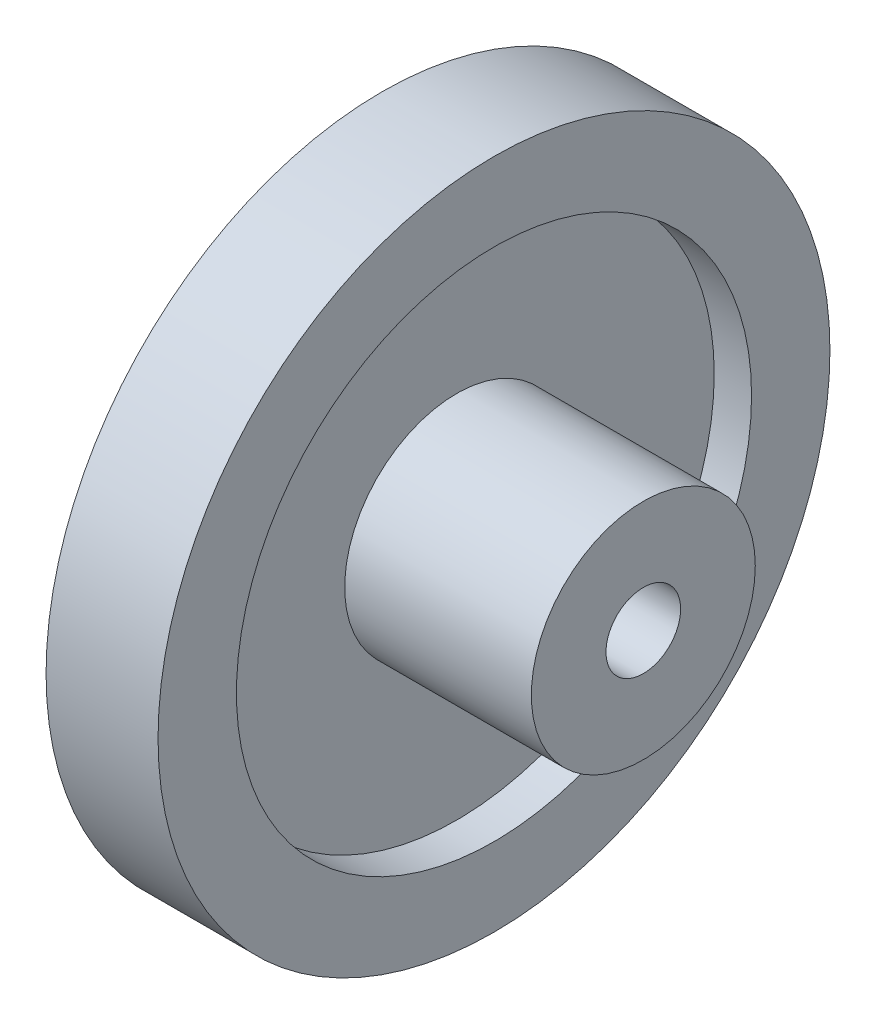
SolidWorks part; units mm, degrees
ref_plane "Plan de face" through (0, 0, 0) normal (0, 0, 1) x (1, 0, 0)
ref_plane "Plan de dessus" through (0, 0, 0) normal (0, 1, 0) x (1, 0, 0)
ref_plane "Plan de droite" through (0, 0, 0) normal (1, 0, 0) x (0, 0, -1)
sketch "Esquisse2" plane through (0, 0, 0) normal (1, 0, 0) x (0, 0, -1)
  arc A0 (8.9927, 0.363) -> (8.9699, 0.736) centre (0, 0) ccw
  arc A1 (8.7729, 2.0092) -> (8.6819, 2.3717) centre (0, 0) ccw
  arc A2 (8.2543, 3.587) -> (8.0983, 3.9266) centre (0, 0) ccw
  arc A3 (7.4547, 5.0426) -> (7.2389, 5.3478) centre (0, 0) ccw
  arc A4 (6.4012, 6.3266) -> (6.133, 6.5869) centre (0, 0) ccw
  arc A5 (5.1297, 7.395) -> (4.8182, 7.6016) centre (0, 0) ccw
  arc A6 (3.6835, 8.2117) -> (3.3394, 8.3575) centre (0, 0) ccw
  arc A7 (2.1119, 8.7487) -> (1.7468, 8.8289) centre (0, 0) ccw
  arc A8 (0.4683, 8.9878) -> (0.0948, 8.9995) centre (0, 0) ccw
  arc A9 (-1.1911, 8.9208) -> (-1.5605, 8.8637) centre (0, 0) ccw
  arc A10 (-2.8101, 8.5501) -> (-3.1626, 8.426) centre (0, 0) ccw
  arc A11 (-4.3333, 7.8881) -> (-4.657, 7.7014) centre (0, 0) ccw
  arc A12 (-5.7089, 6.9576) -> (-5.9929, 6.7146) centre (0, 0) ccw
  arc A13 (-6.8902, 5.7901) -> (-7.1246, 5.499) centre (0, 0) ccw
  arc A14 (-7.8368, 4.4254) -> (-8.0138, 4.0963) centre (0, 0) ccw
  arc A15 (-8.5165, 2.9101) -> (-8.63, 2.554) centre (0, 0) ccw
  arc A16 (-8.9063, 1.2956) -> (-8.9524, 0.9247) centre (0, 0) ccw
  arc A17 (-8.9927, -0.363) -> (-8.9699, -0.736) centre (0, 0) ccw
  arc A18 (-8.7729, -2.0092) -> (-8.6819, -2.3717) centre (0, 0) ccw
  arc A19 (-8.2543, -3.587) -> (-8.0983, -3.9266) centre (0, 0) ccw
  arc A20 (-7.4547, -5.0426) -> (-7.2389, -5.3478) centre (0, 0) ccw
  arc A21 (-6.4012, -6.3266) -> (-6.133, -6.5869) centre (0, 0) ccw
  arc A22 (-5.1297, -7.395) -> (-4.8182, -7.6016) centre (0, 0) ccw
  arc A23 (-3.6835, -8.2117) -> (-3.3394, -8.3575) centre (0, 0) ccw
  arc A24 (-2.1119, -8.7487) -> (-1.7468, -8.8289) centre (0, 0) ccw
  arc A25 (-0.4683, -8.9878) -> (-0.0948, -8.9995) centre (0, 0) ccw
  arc A26 (1.1911, -8.9208) -> (1.5605, -8.8637) centre (0, 0) ccw
  arc A27 (2.8101, -8.5501) -> (3.1626, -8.426) centre (0, 0) ccw
  arc A28 (4.3333, -7.8881) -> (4.657, -7.7014) centre (0, 0) ccw
  arc A29 (5.7089, -6.9576) -> (5.9929, -6.7146) centre (0, 0) ccw
  arc A30 (6.8902, -5.7901) -> (7.1246, -5.499) centre (0, 0) ccw
  arc A31 (7.8368, -4.4254) -> (8.0138, -4.0963) centre (0, 0) ccw
  arc A32 (8.5165, -2.9101) -> (8.63, -2.554) centre (0, 0) ccw
  arc A33 (8.9063, -1.2956) -> (8.9524, -0.9247) centre (0, 0) ccw
  arc A34 (7.987, 0) -> (7.8742, -0.1109) centre (7.9867, -0.1125) ccw
  arc A35 (7.8657, -0.3818) -> (7.9719, -0.4996) centre (7.9781, -0.3873) ccw
  arc A36 (7.8657, -0.3818) -> (7.8742, -0.1109) centre (0, 0) ccw
  arc A37 (7.851, 1.4676) -> (7.7605, 1.3379) centre (7.8714, 1.357) ccw
  arc A38 (7.802, 1.07) -> (7.928, 0.9737) centre (7.9134, 1.0853) ccw
  arc A39 (7.802, 1.07) -> (7.7605, 1.3379) centre (0, 0) ccw
  arc A40 (7.4477, 2.8852) -> (7.3826, 2.7411) centre (7.488, 2.7802) ccw
  arc A41 (7.4725, 2.4854) -> (7.6141, 2.4139) centre (7.5793, 2.5209) ccw
  arc A42 (7.4725, 2.4854) -> (7.3826, 2.7411) centre (0, 0) ccw
  arc A43 (6.7907, 4.2046) -> (6.7532, 4.0509) centre (6.8497, 4.1088) ccw
  arc A44 (6.8886, 3.8161) -> (7.0409, 3.7719) centre (6.987, 3.8706) ccw
  arc A45 (6.8886, 3.8161) -> (6.7532, 4.0509) centre (0, 0) ccw
  arc A46 (5.9025, 5.3808) -> (5.8938, 5.2229) centre (5.978, 5.2975) ccw
  arc A47 (6.0701, 5.0169) -> (6.2279, 5.0014) centre (6.1568, 5.0886) ccw
  arc A48 (6.0701, 5.0169) -> (5.8938, 5.2229) centre (0, 0) ccw
  arc A49 (4.8132, 6.3738) -> (4.8338, 6.2169) centre (4.9028, 6.3057) ccw
  arc A50 (5.0449, 6.0469) -> (5.2029, 6.0607) centre (5.117, 6.1333) ccw
  arc A51 (5.0449, 6.0469) -> (4.8338, 6.2169) centre (0, 0) ccw
  arc A52 (3.5601, 7.1497) -> (3.6091, 6.9993) centre (3.6607, 7.0993) ccw
  arc A53 (3.8479, 6.8709) -> (4.0007, 6.9135) centre (3.9028, 6.9691) ccw
  arc A54 (3.8479, 6.8709) -> (3.6091, 6.9993) centre (0, 0) ccw
  arc A55 (2.1857, 7.6821) -> (2.2616, 7.5433) centre (2.2939, 7.651) ccw
  arc A56 (2.5198, 7.461) -> (2.6622, 7.5309) centre (2.5558, 7.5676) ccw
  arc A57 (2.5198, 7.461) -> (2.2616, 7.5433) centre (0, 0) ccw
  arc A58 (0.7369, 7.9529) -> (0.837, 7.8304) centre (0.8489, 7.9423) ccw
  arc A59 (1.106, 7.797) -> (1.2331, 7.8918) centre (1.1218, 7.9083) ccw
  arc A60 (1.106, 7.797) -> (0.837, 7.8304) centre (0, 0) ccw
  arc A61 (-0.7369, 7.9529) -> (-0.6161, 7.8509) centre (-0.6249, 7.963) ccw
  arc A62 (-0.3455, 7.8674) -> (-0.2381, 7.984) centre (-0.3505, 7.9798) ccw
  arc A63 (-0.3455, 7.8674) -> (-0.6161, 7.8509) centre (0, 0) ccw
  arc A64 (-2.1857, 7.6821) -> (-2.0482, 7.604) centre (-2.0775, 7.7126) ccw
  arc A65 (-1.7853, 7.67) -> (-1.7011, 7.8044) centre (-1.8108, 7.7795) ccw
  arc A66 (-1.7853, 7.67) -> (-2.0482, 7.604) centre (0, 0) ccw
  arc A67 (-3.5601, 7.1497) -> (-3.4106, 7.0981) centre (-3.4593, 7.1996) ccw
  arc A68 (-3.1642, 7.2113) -> (-3.1062, 7.3589) centre (-3.2095, 7.3143) ccw
  arc A69 (-3.1642, 7.2113) -> (-3.4106, 7.0981) centre (0, 0) ccw
  arc A70 (-4.8132, 6.3738) -> (-4.6568, 6.3506) centre (-4.7233, 6.4413) ccw
  arc A71 (-4.4354, 6.5071) -> (-4.4055, 6.6628) centre (-4.4988, 6.6001) ccw
  arc A72 (-4.4354, 6.5071) -> (-4.6568, 6.3506) centre (0, 0) ccw
  arc A73 (-5.9025, 5.3808) -> (-5.7444, 5.3868) centre (-5.8265, 5.4637) ccw
  arc A74 (-5.5556, 5.5813) -> (-5.5547, 5.7399) centre (-5.635, 5.661) ccw
  arc A75 (-5.5556, 5.5813) -> (-5.7444, 5.3868) centre (0, 0) ccw
  arc A76 (-6.7907, 4.2046) -> (-6.6364, 4.2395) centre (-6.7312, 4.3001) ccw
  arc A77 (-6.4866, 4.4654) -> (-6.5149, 4.6215) centre (-6.5792, 4.5292) ccw
  arc A78 (-6.4866, 4.4654) -> (-6.6364, 4.2395) centre (0, 0) ccw
  arc A79 (-7.4477, 2.8852) -> (-7.3024, 2.9479) centre (-7.4067, 2.99) ccw
  arc A80 (-7.1966, 3.1975) -> (-7.2531, 3.3457) centre (-7.2995, 3.2432) ccw
  arc A81 (-7.1966, 3.1975) -> (-7.3024, 2.9479) centre (0, 0) ccw
  arc A82 (-7.851, 1.4676) -> (-7.7198, 1.5559) centre (-7.83, 1.5781) ccw
  arc A83 (-7.6616, 1.8207) -> (-7.7444, 1.956) centre (-7.7711, 1.8467) ccw
  arc A84 (-7.6616, 1.8207) -> (-7.7198, 1.5559) centre (0, 0) ccw
  arc A85 (-7.987, 0) -> (-7.8742, 0.1109) centre (-7.9867, 0.1125) ccw
  arc A86 (-7.8657, 0.3818) -> (-7.9719, 0.4996) centre (-7.9781, 0.3873) ccw
  arc A87 (-7.8657, 0.3818) -> (-7.8742, 0.1109) centre (0, 0) ccw
  arc A88 (-7.851, -1.4676) -> (-7.7605, -1.3379) centre (-7.8714, -1.357) ccw
  arc A89 (-7.802, -1.07) -> (-7.928, -0.9737) centre (-7.9134, -1.0853) ccw
  arc A90 (-7.802, -1.07) -> (-7.7605, -1.3379) centre (0, 0) ccw
  arc A91 (-7.4477, -2.8852) -> (-7.3826, -2.7411) centre (-7.488, -2.7802) ccw
  arc A92 (-7.4725, -2.4854) -> (-7.6141, -2.4139) centre (-7.5793, -2.5209) ccw
  arc A93 (-7.4725, -2.4854) -> (-7.3826, -2.7411) centre (0, 0) ccw
  arc A94 (-6.7907, -4.2046) -> (-6.7532, -4.0509) centre (-6.8497, -4.1088) ccw
  arc A95 (-6.8886, -3.8161) -> (-7.0409, -3.7719) centre (-6.987, -3.8706) ccw
  arc A96 (-6.8886, -3.8161) -> (-6.7532, -4.0509) centre (0, 0) ccw
  arc A97 (-5.9025, -5.3808) -> (-5.8938, -5.2229) centre (-5.978, -5.2975) ccw
  arc A98 (-6.0701, -5.0169) -> (-6.2279, -5.0014) centre (-6.1568, -5.0886) ccw
  arc A99 (-6.0701, -5.0169) -> (-5.8938, -5.2229) centre (0, 0) ccw
  arc A100 (-4.8132, -6.3738) -> (-4.8338, -6.2169) centre (-4.9028, -6.3057) ccw
  arc A101 (-5.0449, -6.0469) -> (-5.2029, -6.0607) centre (-5.117, -6.1333) ccw
  arc A102 (-5.0449, -6.0469) -> (-4.8338, -6.2169) centre (0, 0) ccw
  arc A103 (-3.5601, -7.1497) -> (-3.6091, -6.9993) centre (-3.6607, -7.0993) ccw
  arc A104 (-3.8479, -6.8709) -> (-4.0007, -6.9135) centre (-3.9028, -6.9691) ccw
  arc A105 (-3.8479, -6.8709) -> (-3.6091, -6.9993) centre (0, 0) ccw
  arc A106 (-2.1857, -7.6821) -> (-2.2616, -7.5433) centre (-2.2939, -7.651) ccw
  arc A107 (-2.5198, -7.461) -> (-2.6622, -7.5309) centre (-2.5558, -7.5676) ccw
  arc A108 (-2.5198, -7.461) -> (-2.2616, -7.5433) centre (0, 0) ccw
  arc A109 (-0.7369, -7.9529) -> (-0.837, -7.8304) centre (-0.8489, -7.9423) ccw
  arc A110 (-1.106, -7.797) -> (-1.2331, -7.8918) centre (-1.1218, -7.9083) ccw
  arc A111 (-1.106, -7.797) -> (-0.837, -7.8304) centre (0, 0) ccw
  arc A112 (0.7369, -7.9529) -> (0.6161, -7.8509) centre (0.6249, -7.963) ccw
  arc A113 (0.3455, -7.8674) -> (0.2381, -7.984) centre (0.3505, -7.9798) ccw
  arc A114 (0.3455, -7.8674) -> (0.6161, -7.8509) centre (0, 0) ccw
  arc A115 (2.1857, -7.6821) -> (2.0482, -7.604) centre (2.0775, -7.7126) ccw
  arc A116 (1.7853, -7.67) -> (1.7011, -7.8044) centre (1.8108, -7.7795) ccw
  arc A117 (1.7853, -7.67) -> (2.0482, -7.604) centre (0, 0) ccw
  arc A118 (3.5601, -7.1497) -> (3.4106, -7.0981) centre (3.4593, -7.1996) ccw
  arc A119 (3.1642, -7.2113) -> (3.1062, -7.3589) centre (3.2095, -7.3143) ccw
  arc A120 (3.1642, -7.2113) -> (3.4106, -7.0981) centre (0, 0) ccw
  arc A121 (4.8132, -6.3738) -> (4.6568, -6.3506) centre (4.7233, -6.4413) ccw
  arc A122 (4.4354, -6.5071) -> (4.4055, -6.6628) centre (4.4988, -6.6001) ccw
  arc A123 (4.4354, -6.5071) -> (4.6568, -6.3506) centre (0, 0) ccw
  arc A124 (5.9025, -5.3808) -> (5.7444, -5.3868) centre (5.8265, -5.4637) ccw
  arc A125 (5.5556, -5.5813) -> (5.5547, -5.7399) centre (5.635, -5.661) ccw
  arc A126 (5.5556, -5.5813) -> (5.7444, -5.3868) centre (0, 0) ccw
  arc A127 (6.7907, -4.2046) -> (6.6364, -4.2395) centre (6.7312, -4.3001) ccw
  arc A128 (6.4866, -4.4654) -> (6.5149, -4.6215) centre (6.5792, -4.5292) ccw
  arc A129 (6.4866, -4.4654) -> (6.6364, -4.2395) centre (0, 0) ccw
  arc A130 (7.4477, -2.8852) -> (7.3024, -2.9479) centre (7.4067, -2.99) ccw
  arc A131 (7.1966, -3.1975) -> (7.2531, -3.3457) centre (7.2995, -3.2432) ccw
  arc A132 (7.1966, -3.1975) -> (7.3024, -2.9479) centre (0, 0) ccw
  arc A133 (7.851, -1.4676) -> (7.7198, -1.5559) centre (7.83, -1.5781) ccw
  arc A134 (7.6616, -1.8207) -> (7.7444, -1.956) centre (7.7711, -1.8467) ccw
  arc A135 (7.6616, -1.8207) -> (7.7198, -1.5559) centre (0, 0) ccw
  circle A136 centre (0, 0) radius 1
  spline S0 degree 3 poles (7.987, 0) (8.0286, 0) (8.2037, 0.0282) (8.4818, 0.1115) (8.7713, 0.2415) (8.9323, 0.3284) (8.9927, 0.363) knots 0 0 0 0 0.124841 0.528779 0.867842 1.076016 1.076016 1.076016 1.076016
  spline S1 degree 3 poles (7.928, 0.9737) (7.9687, 0.9787) (8.146, 0.9721) (8.4321, 0.9233) (8.7354, 0.8295) (8.9058, 0.7629) (8.9699, 0.736) knots 0 0 0 0 0.124841 0.528779 0.867842 1.076016 1.076016 1.076016 1.076016
  spline S2 degree 3 poles (7.851, 1.4676) (7.8919, 1.4753) (8.0589, 1.5352) (8.3169, 1.6682) (8.5776, 1.8491) (8.7199, 1.9642) (8.7729, 2.0092) knots 0 0 0 0 0.124841 0.528779 0.867842 1.076016 1.076016 1.076016 1.076016
  spline S3 degree 3 poles (7.6141, 2.4139) (7.6532, 2.4263) (7.8287, 2.4523) (8.1189, 2.4569) (8.4342, 2.4205) (8.6139, 2.3863) (8.6819, 2.3717) knots 0 0 0 0 0.124841 0.528779 0.867842 1.076016 1.076016 1.076016 1.076016
  spline S4 degree 3 poles (7.4477, 2.8852) (7.4865, 2.9003) (7.6396, 2.9898) (7.8687, 3.168) (8.0918, 3.3938) (8.2105, 3.533) (8.2543, 3.587) knots 0 0 0 0 0.124841 0.528779 0.867842 1.076016 1.076016 1.076016 1.076016
  spline S5 degree 3 poles (7.0409, 3.7719) (7.0771, 3.7913) (7.2448, 3.8491) (7.5292, 3.9069) (7.8458, 3.9291) (8.0288, 3.9285) (8.0983, 3.9266) knots 0 0 0 0 0.124841 0.528779 0.867842 1.076016 1.076016 1.076016 1.076016
  spline S6 degree 3 poles (6.7907, 4.2046) (6.8261, 4.2265) (6.9601, 4.3427) (7.1526, 4.5599) (7.3304, 4.8229) (7.4215, 4.9815) (7.4547, 5.0426) knots 0 0 0 0 0.124841 0.528779 0.867842 1.076016 1.076016 1.076016 1.076016
  spline S7 degree 3 poles (6.2279, 5.0014) (6.2599, 5.0271) (6.4141, 5.1148) (6.6831, 5.2239) (6.9903, 5.3039) (7.1702, 5.3369) (7.2389, 5.3478) knots 0 0 0 0 0.124841 0.528779 0.867842 1.076016 1.076016 1.076016 1.076016
  spline S8 degree 3 poles (5.9025, 5.3808) (5.9332, 5.4088) (6.0436, 5.5477) (6.193, 5.7966) (6.3194, 6.0877) (6.3798, 6.2604) (6.4012, 6.3266) knots 0 0 0 0 0.124841 0.528779 0.867842 1.076016 1.076016 1.076016 1.076016
  spline S9 degree 3 poles (5.2029, 6.0607) (5.2296, 6.0918) (5.3651, 6.2063) (5.6094, 6.363) (5.8967, 6.498) (6.0675, 6.5636) (6.133, 6.5869) knots 0 0 0 0 0.124841 0.528779 0.867842 1.076016 1.076016 1.076016 1.076016
  spline S10 degree 3 poles (4.8132, 6.3738) (4.8383, 6.407) (4.9213, 6.5637) (5.0224, 6.8358) (5.0932, 7.1452) (5.1208, 7.3261) (5.1297, 7.395) knots 0 0 0 0 0.124841 0.528779 0.867842 1.076016 1.076016 1.076016 1.076016
  spline S11 degree 3 poles (4.0007, 6.9135) (4.0212, 6.949) (4.1333, 7.0864) (4.3447, 7.2854) (4.6022, 7.4709) (4.7581, 7.5667) (4.8182, 7.6016) knots 0 0 0 0 0.124841 0.528779 0.867842 1.076016 1.076016 1.076016 1.076016
  spline S12 degree 3 poles (3.5601, 7.1497) (3.5787, 7.1869) (3.6315, 7.3563) (3.6808, 7.6423) (3.6935, 7.9594) (3.6875, 8.1423) (3.6835, 8.2117) knots 0 0 0 0 0.124841 0.528779 0.867842 1.076016 1.076016 1.076016 1.076016
  spline S13 degree 3 poles (2.6622, 7.5309) (2.6759, 7.5696) (2.7608, 7.7253) (2.932, 7.9596) (3.1511, 8.1893) (3.2867, 8.3122) (3.3394, 8.3575) knots 0 0 0 0 0.124841 0.528779 0.867842 1.076016 1.076016 1.076016 1.076016
  spline S14 degree 3 poles (2.1857, 7.6821) (2.1971, 7.7221) (2.2179, 7.8983) (2.2139, 8.1885) (2.1681, 8.5026) (2.1286, 8.6812) (2.1119, 8.7487) knots 0 0 0 0 0.124841 0.528779 0.867842 1.076016 1.076016 1.076016 1.076016
  spline S15 degree 3 poles (1.2331, 7.8918) (1.2394, 7.9324) (1.2943, 8.101) (1.4195, 8.3629) (1.5927, 8.6289) (1.7034, 8.7746) (1.7468, 8.8289) knots 0 0 0 0 0.124841 0.528779 0.867842 1.076016 1.076016 1.076016 1.076016
  spline S16 degree 3 poles (0.7369, 7.9529) (0.7408, 7.9944) (0.7288, 8.1713) (0.6715, 8.4559) (0.5688, 8.7562) (0.4971, 8.9245) (0.4683, 8.9878) knots 0 0 0 0 0.124841 0.528779 0.867842 1.076016 1.076016 1.076016 1.076016
  spline S17 degree 3 poles (-0.2381, 7.984) (-0.2393, 8.025) (-0.2163, 8.2009) (-0.1413, 8.4813) (-0.02, 8.7746) (0.0621, 8.9382) (0.0948, 8.9995) knots 0 0 0 0 0.124841 0.528779 0.867842 1.076016 1.076016 1.076016 1.076016
  spline S18 degree 3 poles (-0.7369, 7.9529) (-0.7408, 7.9944) (-0.785, 8.1661) (-0.8937, 8.4353) (-1.0498, 8.7116) (-1.1512, 8.8639) (-1.1911, 8.9208) knots 0 0 0 0 0.124841 0.528779 0.867842 1.076016 1.076016 1.076016 1.076016
  spline S19 degree 3 poles (-1.7011, 7.8044) (-1.7098, 7.8444) (-1.7195, 8.0216) (-1.6973, 8.311) (-1.632, 8.6216) (-1.5814, 8.7974) (-1.5605, 8.8637) knots 0 0 0 0 0.124841 0.528779 0.867842 1.076016 1.076016 1.076016 1.076016
  spline S20 degree 3 poles (-2.1857, 7.6821) (-2.1971, 7.7221) (-2.2722, 7.8828) (-2.4284, 8.1275) (-2.6327, 8.3704) (-2.7603, 8.5015) (-2.8101, 8.5501) knots 0 0 0 0 0.124841 0.528779 0.867842 1.076016 1.076016 1.076016 1.076016
  spline S21 degree 3 poles (-3.1062, 7.3589) (-3.1221, 7.3967) (-3.1642, 7.569) (-3.1956, 7.8576) (-3.1884, 8.1749) (-3.171, 8.357) (-3.1626, 8.426) knots 0 0 0 0 0.124841 0.528779 0.867842 1.076016 1.076016 1.076016 1.076016
  spline S22 degree 3 poles (-3.5601, 7.1497) (-3.5787, 7.1869) (-3.682, 7.3311) (-3.8805, 7.5429) (-4.1259, 7.7441) (-4.2755, 7.8495) (-4.3333, 7.8881) knots 0 0 0 0 0.124841 0.528779 0.867842 1.076016 1.076016 1.076016 1.076016
  spline S23 degree 3 poles (-4.4055, 6.6628) (-4.4281, 6.6971) (-4.5011, 6.8587) (-4.585, 7.1366) (-4.6363, 7.4498) (-4.6526, 7.6321) (-4.657, 7.7014) knots 0 0 0 0 0.124841 0.528779 0.867842 1.076016 1.076016 1.076016 1.076016
  spline S24 degree 3 poles (-4.8132, 6.3738) (-4.8383, 6.407) (-4.9664, 6.5297) (-5.2004, 6.7014) (-5.4787, 6.8541) (-5.645, 6.9302) (-5.7089, 6.9576) knots 0 0 0 0 0.124841 0.528779 0.867842 1.076016 1.076016 1.076016 1.076016
  spline S25 degree 3 poles (-5.5547, 5.7399) (-5.5833, 5.7694) (-5.6848, 5.9148) (-5.8183, 6.1726) (-5.9262, 6.4711) (-5.9757, 6.6472) (-5.9929, 6.7146) knots 0 0 0 0 0.124841 0.528779 0.867842 1.076016 1.076016 1.076016 1.076016
  spline S26 degree 3 poles (-5.9025, 5.3808) (-5.9332, 5.4088) (-6.0816, 5.506) (-6.3432, 5.6317) (-6.6448, 5.7307) (-6.8223, 5.775) (-6.8902, 5.7901) knots 0 0 0 0 0.124841 0.528779 0.867842 1.076016 1.076016 1.076016 1.076016
  spline S27 degree 3 poles (-6.5149, 4.6215) (-6.5483, 4.6452) (-6.6748, 4.7696) (-6.8534, 4.9984) (-7.0144, 5.2719) (-7.0954, 5.436) (-7.1246, 5.499) knots 0 0 0 0 0.124841 0.528779 0.867842 1.076016 1.076016 1.076016 1.076016
  spline S28 degree 3 poles (-6.7907, 4.2046) (-6.8261, 4.2265) (-6.9898, 4.2947) (-7.2701, 4.3703) (-7.5847, 4.4122) (-7.7673, 4.423) (-7.8368, 4.4254) knots 0 0 0 0 0.124841 0.528779 0.867842 1.076016 1.076016 1.076016 1.076016
  spline S29 degree 3 poles (-7.2531, 3.3457) (-7.2904, 3.3629) (-7.4376, 3.4619) (-7.6552, 3.654) (-7.8637, 3.8933) (-7.9735, 4.0396) (-8.0138, 4.0963) knots 0 0 0 0 0.124841 0.528779 0.867842 1.076016 1.076016 1.076016 1.076016
  spline S30 degree 3 poles (-7.4477, 2.8852) (-7.4865, 2.9003) (-7.66, 2.9372) (-7.9493, 2.96) (-8.2663, 2.9434) (-8.4478, 2.9205) (-8.5165, 2.9101) knots 0 0 0 0 0.124841 0.528779 0.867842 1.076016 1.076016 1.076016 1.076016
  spline S31 degree 3 poles (-7.7444, 1.956) (-7.7842, 1.966) (-7.9471, 2.0363) (-8.1962, 2.1851) (-8.4452, 2.3821) (-8.58, 2.5057) (-8.63, 2.554) knots 0 0 0 0 0.124841 0.528779 0.867842 1.076016 1.076016 1.076016 1.076016
  spline S32 degree 3 poles (-7.851, 1.4676) (-7.8919, 1.4753) (-8.0692, 1.4797) (-8.3578, 1.4489) (-8.6664, 1.3743) (-8.8406, 1.3185) (-8.9063, 1.2956) knots 0 0 0 0 0.124841 0.528779 0.867842 1.076016 1.076016 1.076016 1.076016
  spline S33 degree 3 poles (-7.9719, 0.4996) (-8.0129, 0.5022) (-8.1859, 0.5413) (-8.4582, 0.6419) (-8.7391, 0.7897) (-8.8943, 0.8865) (-8.9524, 0.9247) knots 0 0 0 0 0.124841 0.528779 0.867842 1.076016 1.076016 1.076016 1.076016
  spline S34 degree 3 poles (-7.987, 0) (-8.0286, 0) (-8.2037, -0.0282) (-8.4818, -0.1115) (-8.7713, -0.2415) (-8.9323, -0.3284) (-8.9927, -0.363) knots 0 0 0 0 0.124841 0.528779 0.867842 1.076016 1.076016 1.076016 1.076016
  spline S35 degree 3 poles (-7.928, -0.9737) (-7.9687, -0.9787) (-8.146, -0.9721) (-8.4321, -0.9233) (-8.7354, -0.8295) (-8.9058, -0.7629) (-8.9699, -0.736) knots 0 0 0 0 0.124841 0.528779 0.867842 1.076016 1.076016 1.076016 1.076016
  spline S36 degree 3 poles (-7.851, -1.4676) (-7.8919, -1.4753) (-8.0589, -1.5352) (-8.3169, -1.6682) (-8.5776, -1.8491) (-8.7199, -1.9642) (-8.7729, -2.0092) knots 0 0 0 0 0.124841 0.528779 0.867842 1.076016 1.076016 1.076016 1.076016
  spline S37 degree 3 poles (-7.6141, -2.4139) (-7.6532, -2.4263) (-7.8287, -2.4523) (-8.1189, -2.4569) (-8.4342, -2.4205) (-8.6139, -2.3863) (-8.6819, -2.3717) knots 0 0 0 0 0.124841 0.528779 0.867842 1.076016 1.076016 1.076016 1.076016
  spline S38 degree 3 poles (-7.4477, -2.8852) (-7.4865, -2.9003) (-7.6396, -2.9898) (-7.8687, -3.168) (-8.0918, -3.3938) (-8.2105, -3.533) (-8.2543, -3.587) knots 0 0 0 0 0.124841 0.528779 0.867842 1.076016 1.076016 1.076016 1.076016
  spline S39 degree 3 poles (-7.0409, -3.7719) (-7.0771, -3.7913) (-7.2448, -3.8491) (-7.5292, -3.9069) (-7.8458, -3.9291) (-8.0288, -3.9285) (-8.0983, -3.9266) knots 0 0 0 0 0.124841 0.528779 0.867842 1.076016 1.076016 1.076016 1.076016
  spline S40 degree 3 poles (-6.7907, -4.2046) (-6.8261, -4.2265) (-6.9601, -4.3427) (-7.1526, -4.5599) (-7.3304, -4.8229) (-7.4215, -4.9815) (-7.4547, -5.0426) knots 0 0 0 0 0.124841 0.528779 0.867842 1.076016 1.076016 1.076016 1.076016
  spline S41 degree 3 poles (-6.2279, -5.0014) (-6.2599, -5.0271) (-6.4141, -5.1148) (-6.6831, -5.2239) (-6.9903, -5.3039) (-7.1702, -5.3369) (-7.2389, -5.3478) knots 0 0 0 0 0.124841 0.528779 0.867842 1.076016 1.076016 1.076016 1.076016
  spline S42 degree 3 poles (-5.9025, -5.3808) (-5.9332, -5.4088) (-6.0436, -5.5477) (-6.193, -5.7966) (-6.3194, -6.0877) (-6.3798, -6.2604) (-6.4012, -6.3266) knots 0 0 0 0 0.124841 0.528779 0.867842 1.076016 1.076016 1.076016 1.076016
  spline S43 degree 3 poles (-5.2029, -6.0607) (-5.2296, -6.0918) (-5.3651, -6.2063) (-5.6094, -6.363) (-5.8967, -6.498) (-6.0675, -6.5636) (-6.133, -6.5869) knots 0 0 0 0 0.124841 0.528779 0.867842 1.076016 1.076016 1.076016 1.076016
  spline S44 degree 3 poles (-4.8132, -6.3738) (-4.8383, -6.407) (-4.9213, -6.5637) (-5.0224, -6.8358) (-5.0932, -7.1452) (-5.1208, -7.3261) (-5.1297, -7.395) knots 0 0 0 0 0.124841 0.528779 0.867842 1.076016 1.076016 1.076016 1.076016
  spline S45 degree 3 poles (-4.0007, -6.9135) (-4.0212, -6.949) (-4.1333, -7.0864) (-4.3447, -7.2854) (-4.6022, -7.4709) (-4.7581, -7.5667) (-4.8182, -7.6016) knots 0 0 0 0 0.124841 0.528779 0.867842 1.076016 1.076016 1.076016 1.076016
  spline S46 degree 3 poles (-3.5601, -7.1497) (-3.5787, -7.1869) (-3.6315, -7.3563) (-3.6808, -7.6423) (-3.6935, -7.9594) (-3.6875, -8.1423) (-3.6835, -8.2117) knots 0 0 0 0 0.124841 0.528779 0.867842 1.076016 1.076016 1.076016 1.076016
  spline S47 degree 3 poles (-2.6622, -7.5309) (-2.6759, -7.5696) (-2.7608, -7.7253) (-2.932, -7.9596) (-3.1511, -8.1893) (-3.2867, -8.3122) (-3.3394, -8.3575) knots 0 0 0 0 0.124841 0.528779 0.867842 1.076016 1.076016 1.076016 1.076016
  spline S48 degree 3 poles (-2.1857, -7.6821) (-2.1971, -7.7221) (-2.2179, -7.8983) (-2.2139, -8.1885) (-2.1681, -8.5026) (-2.1286, -8.6812) (-2.1119, -8.7487) knots 0 0 0 0 0.124841 0.528779 0.867842 1.076016 1.076016 1.076016 1.076016
  spline S49 degree 3 poles (-1.2331, -7.8918) (-1.2394, -7.9324) (-1.2943, -8.101) (-1.4195, -8.3629) (-1.5927, -8.6289) (-1.7034, -8.7746) (-1.7468, -8.8289) knots 0 0 0 0 0.124841 0.528779 0.867842 1.076016 1.076016 1.076016 1.076016
  spline S50 degree 3 poles (-0.7369, -7.9529) (-0.7408, -7.9944) (-0.7288, -8.1713) (-0.6715, -8.4559) (-0.5688, -8.7562) (-0.4971, -8.9245) (-0.4683, -8.9878) knots 0 0 0 0 0.124841 0.528779 0.867842 1.076016 1.076016 1.076016 1.076016
  spline S51 degree 3 poles (0.2381, -7.984) (0.2393, -8.025) (0.2163, -8.2009) (0.1413, -8.4813) (0.02, -8.7746) (-0.0621, -8.9382) (-0.0948, -8.9995) knots 0 0 0 0 0.124841 0.528779 0.867842 1.076016 1.076016 1.076016 1.076016
  spline S52 degree 3 poles (0.7369, -7.9529) (0.7408, -7.9944) (0.785, -8.1661) (0.8937, -8.4353) (1.0498, -8.7116) (1.1512, -8.8639) (1.1911, -8.9208) knots 0 0 0 0 0.124841 0.528779 0.867842 1.076016 1.076016 1.076016 1.076016
  spline S53 degree 3 poles (1.7011, -7.8044) (1.7098, -7.8444) (1.7195, -8.0216) (1.6973, -8.311) (1.632, -8.6216) (1.5814, -8.7974) (1.5605, -8.8637) knots 0 0 0 0 0.124841 0.528779 0.867842 1.076016 1.076016 1.076016 1.076016
  spline S54 degree 3 poles (2.1857, -7.6821) (2.1971, -7.7221) (2.2722, -7.8828) (2.4284, -8.1275) (2.6327, -8.3704) (2.7603, -8.5015) (2.8101, -8.5501) knots 0 0 0 0 0.124841 0.528779 0.867842 1.076016 1.076016 1.076016 1.076016
  spline S55 degree 3 poles (3.1062, -7.3589) (3.1221, -7.3967) (3.1642, -7.569) (3.1956, -7.8576) (3.1884, -8.1749) (3.171, -8.357) (3.1626, -8.426) knots 0 0 0 0 0.124841 0.528779 0.867842 1.076016 1.076016 1.076016 1.076016
  spline S56 degree 3 poles (3.5601, -7.1497) (3.5787, -7.1869) (3.682, -7.3311) (3.8805, -7.5429) (4.1259, -7.7441) (4.2755, -7.8495) (4.3333, -7.8881) knots 0 0 0 0 0.124841 0.528779 0.867842 1.076016 1.076016 1.076016 1.076016
  spline S57 degree 3 poles (4.4055, -6.6628) (4.4281, -6.6971) (4.5011, -6.8587) (4.585, -7.1366) (4.6363, -7.4498) (4.6526, -7.6321) (4.657, -7.7014) knots 0 0 0 0 0.124841 0.528779 0.867842 1.076016 1.076016 1.076016 1.076016
  spline S58 degree 3 poles (4.8132, -6.3738) (4.8383, -6.407) (4.9664, -6.5297) (5.2004, -6.7014) (5.4787, -6.8541) (5.645, -6.9302) (5.7089, -6.9576) knots 0 0 0 0 0.124841 0.528779 0.867842 1.076016 1.076016 1.076016 1.076016
  spline S59 degree 3 poles (5.5547, -5.7399) (5.5833, -5.7694) (5.6848, -5.9148) (5.8183, -6.1726) (5.9262, -6.4711) (5.9757, -6.6472) (5.9929, -6.7146) knots 0 0 0 0 0.124841 0.528779 0.867842 1.076016 1.076016 1.076016 1.076016
  spline S60 degree 3 poles (5.9025, -5.3808) (5.9332, -5.4088) (6.0816, -5.506) (6.3432, -5.6317) (6.6448, -5.7307) (6.8223, -5.775) (6.8902, -5.7901) knots 0 0 0 0 0.124841 0.528779 0.867842 1.076016 1.076016 1.076016 1.076016
  spline S61 degree 3 poles (6.5149, -4.6215) (6.5483, -4.6452) (6.6748, -4.7696) (6.8534, -4.9984) (7.0144, -5.2719) (7.0954, -5.436) (7.1246, -5.499) knots 0 0 0 0 0.124841 0.528779 0.867842 1.076016 1.076016 1.076016 1.076016
  spline S62 degree 3 poles (6.7907, -4.2046) (6.8261, -4.2265) (6.9898, -4.2947) (7.2701, -4.3703) (7.5847, -4.4122) (7.7673, -4.423) (7.8368, -4.4254) knots 0 0 0 0 0.124841 0.528779 0.867842 1.076016 1.076016 1.076016 1.076016
  spline S63 degree 3 poles (7.2531, -3.3457) (7.2904, -3.3629) (7.4376, -3.4619) (7.6552, -3.654) (7.8637, -3.8933) (7.9735, -4.0396) (8.0138, -4.0963) knots 0 0 0 0 0.124841 0.528779 0.867842 1.076016 1.076016 1.076016 1.076016
  spline S64 degree 3 poles (7.4477, -2.8852) (7.4865, -2.9003) (7.66, -2.9372) (7.9493, -2.96) (8.2663, -2.9434) (8.4478, -2.9205) (8.5165, -2.9101) knots 0 0 0 0 0.124841 0.528779 0.867842 1.076016 1.076016 1.076016 1.076016
  spline S65 degree 3 poles (7.7444, -1.956) (7.7842, -1.966) (7.9471, -2.0363) (8.1962, -2.1851) (8.4452, -2.3821) (8.58, -2.5057) (8.63, -2.554) knots 0 0 0 0 0.124841 0.528779 0.867842 1.076016 1.076016 1.076016 1.076016
  spline S66 degree 3 poles (7.851, -1.4676) (7.8919, -1.4753) (8.0692, -1.4797) (8.3578, -1.4489) (8.6664, -1.3743) (8.8406, -1.3185) (8.9063, -1.2956) knots 0 0 0 0 0.124841 0.528779 0.867842 1.076016 1.076016 1.076016 1.076016
  spline S67 degree 3 poles (7.9719, -0.4996) (8.0129, -0.5022) (8.1859, -0.5413) (8.4582, -0.6419) (8.7391, -0.7897) (8.8943, -0.8865) (8.9524, -0.9247) knots 0 0 0 0 0.124841 0.528779 0.867842 1.076016 1.076016 1.076016 1.076016
  dimension "D1" = 2
extrude "Boss.-Extru.1" add sketch "Esquisse2" along normal blind 3
sketch "Esquisse3" plane through (3, 0, 0) normal (1, 0, 0) x (0, 0, -1)
  circle A0 centre (0, 0) radius 6.9
  dimension "D1" = 13.8
extrude "Enlèv. mat.-Extru.1" cut sketch "Esquisse3" against normal blind 1
sketch "Esquisse4" plane through (2, 0, 0) normal (1, 0, 0) x (0, 0, -1)
  arc A0 (2.9773, 0.3683) -> (2.9271, 0.6573) centre (0, 0) ccw
  arc A1 (2.1922, 2.048) -> (1.9817, 2.2523) centre (0, 0) ccw
  arc A2 (0.5698, 2.9454) -> (0.2794, 2.987) centre (0, 0) ccw
  arc A3 (-1.2703, 2.7178) -> (-1.5297, 2.5807) centre (0, 0) ccw
  arc A4 (-2.6252, 1.4521) -> (-2.7544, 1.1887) centre (0, 0) ccw
  arc A5 (-2.9773, -0.3683) -> (-2.9271, -0.6573) centre (0, 0) ccw
  arc A6 (-2.1922, -2.048) -> (-1.9817, -2.2523) centre (0, 0) ccw
  arc A7 (-0.5698, -2.9454) -> (-0.2794, -2.987) centre (0, 0) ccw
  arc A8 (1.2703, -2.7178) -> (1.5297, -2.5807) centre (0, 0) ccw
  arc A9 (2.6252, -1.4521) -> (2.7544, -1.1887) centre (0, 0) ccw
  arc A10 (1.8368, -0.3764) -> (1.8687, -0.154) centre (0, 0) ccw
  arc A11 (1.7073, 0.7751) -> (1.6023, 0.9738) centre (0, 0) ccw
  arc A12 (0.9256, 1.6306) -> (0.7239, 1.7296) centre (0, 0) ccw
  arc A13 (-0.2096, 1.8632) -> (-0.431, 1.8248) centre (0, 0) ccw
  arc A14 (-1.2648, 1.3842) -> (-1.4213, 1.2229) centre (0, 0) ccw
  arc A15 (-1.8368, 0.3764) -> (-1.8687, 0.154) centre (0, 0) ccw
  arc A16 (-1.7073, -0.7751) -> (-1.6023, -0.9738) centre (0, 0) ccw
  arc A17 (-0.9256, -1.6306) -> (-0.7239, -1.7296) centre (0, 0) ccw
  arc A18 (0.2096, -1.8632) -> (0.431, -1.8248) centre (0, 0) ccw
  arc A19 (1.2648, -1.3842) -> (1.4213, -1.2229) centre (0, 0) ccw
  circle A20 centre (0, 0) radius 1
  spline S0 degree 3 poles (2.349, 0) (2.3611, 0) (2.4126, 0.0085) (2.4945, 0.0326) (2.6584, 0.1065) (2.823, 0.2207) (2.9394, 0.3292) (2.9773, 0.3683) knots 0 0 0 0 0.036251 0.155621 0.255291 0.575255 0.744085 0.744085 0.744085 0.744085
  spline S1 degree 3 poles (2.2114, 0.7921) (2.2228, 0.7962) (2.2741, 0.8056) (2.3594, 0.8105) (2.5386, 0.7962) (2.7321, 0.7442) (2.8782, 0.6813) (2.9271, 0.6573) knots 0 0 0 0 0.036251 0.155621 0.255291 0.575255 0.744085 0.744085 0.744085 0.744085
  spline S2 degree 3 poles (1.9004, 1.3807) (1.9102, 1.3878) (1.9469, 1.4249) (1.9989, 1.4926) (2.0881, 1.6487) (2.1541, 1.8379) (2.1845, 1.9941) (2.1922, 2.048) knots 0 0 0 0 0.036251 0.155621 0.255291 0.575255 0.744085 0.744085 0.744085 0.744085
  spline S3 degree 3 poles (1.3235, 1.9407) (1.3303, 1.9507) (1.3663, 1.9885) (1.4324, 2.0425) (1.5858, 2.1363) (1.7728, 2.2079) (1.9281, 2.243) (1.9817, 2.2523) knots 0 0 0 0 0.036251 0.155621 0.255291 0.575255 0.744085 0.744085 0.744085 0.744085
  spline S4 degree 3 poles (0.7259, 2.234) (0.7296, 2.2455) (0.7375, 2.2971) (0.7398, 2.3825) (0.7202, 2.5612) (0.6625, 2.753) (0.5952, 2.8973) (0.5698, 2.9454) knots 0 0 0 0 0.036251 0.155621 0.255291 0.575255 0.744085 0.744085 0.744085 0.744085
  spline S5 degree 3 poles (-0.07, 2.348) (-0.0704, 2.36) (-0.0634, 2.4118) (-0.0417, 2.4943) (0.0272, 2.6604) (0.1365, 2.8283) (0.2415, 2.9479) (0.2794, 2.987) knots 0 0 0 0 0.036251 0.155621 0.255291 0.575255 0.744085 0.744085 0.744085 0.744085
  spline S6 degree 3 poles (-0.7259, 2.234) (-0.7296, 2.2455) (-0.7536, 2.2919) (-0.8019, 2.3623) (-0.9228, 2.4954) (-1.0823, 2.6166) (-1.2215, 2.6938) (-1.2703, 2.7178) knots 0 0 0 0 0.036251 0.155621 0.255291 0.575255 0.744085 0.744085 0.744085 0.744085
  spline S7 degree 3 poles (-1.4367, 1.8584) (-1.4441, 1.8679) (-1.4689, 1.9139) (-1.4999, 1.9934) (-1.5417, 2.1683) (-1.552, 2.3684) (-1.5374, 2.5268) (-1.5297, 2.5807) knots 0 0 0 0 0.036251 0.155621 0.255291 0.575255 0.744085 0.744085 0.744085 0.744085
  spline S8 degree 3 poles (-1.9004, 1.3807) (-1.9102, 1.3878) (-1.9568, 1.4112) (-2.0373, 1.4398) (-2.2133, 1.4764) (-2.4136, 1.4808) (-2.5715, 1.4614) (-2.6252, 1.4521) knots 0 0 0 0 0.036251 0.155621 0.255291 0.575255 0.744085 0.744085 0.744085 0.744085
  spline S9 degree 3 poles (-2.2547, 0.659) (-2.2663, 0.6624) (-2.3133, 0.6849) (-2.3852, 0.7311) (-2.5218, 0.848) (-2.6477, 1.0038) (-2.729, 1.1406) (-2.7544, 1.1887) knots 0 0 0 0 0.036251 0.155621 0.255291 0.575255 0.744085 0.744085 0.744085 0.744085
  spline S10 degree 3 poles (-2.349, 0) (-2.3611, 0) (-2.4126, -0.0085) (-2.4945, -0.0326) (-2.6584, -0.1065) (-2.823, -0.2207) (-2.9394, -0.3292) (-2.9773, -0.3683) knots 0 0 0 0 0.036251 0.155621 0.255291 0.575255 0.744085 0.744085 0.744085 0.744085
  spline S11 degree 3 poles (-2.2114, -0.7921) (-2.2228, -0.7962) (-2.2741, -0.8056) (-2.3594, -0.8105) (-2.5386, -0.7962) (-2.7321, -0.7442) (-2.8782, -0.6813) (-2.9271, -0.6573) knots 0 0 0 0 0.036251 0.155621 0.255291 0.575255 0.744085 0.744085 0.744085 0.744085
  spline S12 degree 3 poles (-1.9004, -1.3807) (-1.9102, -1.3878) (-1.9469, -1.4249) (-1.9989, -1.4926) (-2.0881, -1.6487) (-2.1541, -1.8379) (-2.1845, -1.9941) (-2.1922, -2.048) knots 0 0 0 0 0.036251 0.155621 0.255291 0.575255 0.744085 0.744085 0.744085 0.744085
  spline S13 degree 3 poles (-1.3235, -1.9407) (-1.3303, -1.9507) (-1.3663, -1.9885) (-1.4324, -2.0425) (-1.5858, -2.1363) (-1.7728, -2.2079) (-1.9281, -2.243) (-1.9817, -2.2523) knots 0 0 0 0 0.036251 0.155621 0.255291 0.575255 0.744085 0.744085 0.744085 0.744085
  spline S14 degree 3 poles (-0.7259, -2.234) (-0.7296, -2.2455) (-0.7375, -2.2971) (-0.7398, -2.3825) (-0.7202, -2.5612) (-0.6625, -2.753) (-0.5952, -2.8973) (-0.5698, -2.9454) knots 0 0 0 0 0.036251 0.155621 0.255291 0.575255 0.744085 0.744085 0.744085 0.744085
  spline S15 degree 3 poles (0.07, -2.348) (0.0704, -2.36) (0.0634, -2.4118) (0.0417, -2.4943) (-0.0272, -2.6604) (-0.1365, -2.8283) (-0.2415, -2.9479) (-0.2794, -2.987) knots 0 0 0 0 0.036251 0.155621 0.255291 0.575255 0.744085 0.744085 0.744085 0.744085
  spline S16 degree 3 poles (0.7259, -2.234) (0.7296, -2.2455) (0.7536, -2.2919) (0.8019, -2.3623) (0.9228, -2.4954) (1.0823, -2.6166) (1.2215, -2.6938) (1.2703, -2.7178) knots 0 0 0 0 0.036251 0.155621 0.255291 0.575255 0.744085 0.744085 0.744085 0.744085
  spline S17 degree 3 poles (1.4367, -1.8584) (1.4441, -1.8679) (1.4689, -1.9139) (1.4999, -1.9934) (1.5417, -2.1683) (1.552, -2.3684) (1.5374, -2.5268) (1.5297, -2.5807) knots 0 0 0 0 0.036251 0.155621 0.255291 0.575255 0.744085 0.744085 0.744085 0.744085
  spline S18 degree 3 poles (1.9004, -1.3807) (1.9102, -1.3878) (1.9568, -1.4112) (2.0373, -1.4398) (2.2133, -1.4764) (2.4136, -1.4808) (2.5715, -1.4614) (2.6252, -1.4521) knots 0 0 0 0 0.036251 0.155621 0.255291 0.575255 0.744085 0.744085 0.744085 0.744085
  spline S19 degree 3 poles (2.2547, -0.659) (2.2663, -0.6624) (2.3133, -0.6849) (2.3852, -0.7311) (2.5218, -0.848) (2.6477, -1.0038) (2.729, -1.1406) (2.7544, -1.1887) knots 0 0 0 0 0.036251 0.155621 0.255291 0.575255 0.744085 0.744085 0.744085 0.744085
  spline S20 degree 3 poles (2.349, 0) (2.2648, 0) (2.1034, 0.0291) (1.8817, -0.0633) (1.8687, -0.154) knots 0 0 0 0 0.252618 0.527509 0.527509 0.527509 0.527509
  spline S21 degree 3 poles (2.2547, -0.659) (2.1739, -0.6353) (2.0108, -0.618) (1.8238, -0.4671) (1.8368, -0.3764) knots 0 0 0 0 0.252618 0.527509 0.527509 0.527509 0.527509
  spline S22 degree 3 poles (1.9004, 1.3807) (1.8323, 1.3312) (1.6846, 1.2599) (1.5595, 1.0548) (1.6023, 0.9738) knots 0 0 0 0 0.252618 0.527509 0.527509 0.527509 0.527509
  spline S23 degree 3 poles (2.2114, 0.7921) (2.1321, 0.7637) (1.99, 0.682) (1.7501, 0.6941) (1.7073, 0.7751) knots 0 0 0 0 0.252618 0.527509 0.527509 0.527509 0.527509
  spline S24 degree 3 poles (0.7259, 2.234) (0.6999, 2.1539) (0.6223, 2.0095) (0.6416, 1.77) (0.7239, 1.7296) knots 0 0 0 0 0.252618 0.527509 0.527509 0.527509 0.527509
  spline S25 degree 3 poles (1.3235, 1.9407) (1.276, 1.8711) (1.2091, 1.7214) (1.0079, 1.5902) (0.9256, 1.6306) knots 0 0 0 0 0.252618 0.527509 0.527509 0.527509 0.527509
  spline S26 degree 3 poles (-0.7259, 2.234) (-0.6999, 2.1539) (-0.6776, 1.9915) (-0.5213, 1.8091) (-0.431, 1.8248) knots 0 0 0 0 0.252618 0.527509 0.527509 0.527509 0.527509
  spline S27 degree 3 poles (-0.07, 2.348) (-0.0675, 2.2638) (-0.0336, 2.1034) (-0.1193, 1.8789) (-0.2096, 1.8632) knots 0 0 0 0 0.252618 0.527509 0.527509 0.527509 0.527509
  spline S28 degree 3 poles (-1.9004, 1.3807) (-1.8323, 1.3312) (-1.7188, 1.2128) (-1.4851, 1.1572) (-1.4213, 1.2229) knots 0 0 0 0 0.252618 0.527509 0.527509 0.527509 0.527509
  spline S29 degree 3 poles (-1.4367, 1.8584) (-1.3852, 1.7918) (-1.2635, 1.6819) (-1.2009, 1.4499) (-1.2648, 1.3842) knots 0 0 0 0 0.252618 0.527509 0.527509 0.527509 0.527509
  spline S30 degree 3 poles (-2.349, 0) (-2.2648, 0) (-2.1034, -0.0291) (-1.8817, 0.0633) (-1.8687, 0.154) knots 0 0 0 0 0.252618 0.527509 0.527509 0.527509 0.527509
  spline S31 degree 3 poles (-2.2547, 0.659) (-2.1739, 0.6353) (-2.0108, 0.618) (-1.8238, 0.4671) (-1.8368, 0.3764) knots 0 0 0 0 0.252618 0.527509 0.527509 0.527509 0.527509
  spline S32 degree 3 poles (-1.9004, -1.3807) (-1.8323, -1.3312) (-1.6846, -1.2599) (-1.5595, -1.0548) (-1.6023, -0.9738) knots 0 0 0 0 0.252618 0.527509 0.527509 0.527509 0.527509
  spline S33 degree 3 poles (-2.2114, -0.7921) (-2.1321, -0.7637) (-1.99, -0.682) (-1.7501, -0.6941) (-1.7073, -0.7751) knots 0 0 0 0 0.252618 0.527509 0.527509 0.527509 0.527509
  spline S34 degree 3 poles (-0.7259, -2.234) (-0.6999, -2.1539) (-0.6223, -2.0095) (-0.6416, -1.77) (-0.7239, -1.7296) knots 0 0 0 0 0.252618 0.527509 0.527509 0.527509 0.527509
  spline S35 degree 3 poles (-1.3235, -1.9407) (-1.276, -1.8711) (-1.2091, -1.7214) (-1.0079, -1.5902) (-0.9256, -1.6306) knots 0 0 0 0 0.252618 0.527509 0.527509 0.527509 0.527509
  spline S36 degree 3 poles (0.7259, -2.234) (0.6999, -2.1539) (0.6776, -1.9915) (0.5213, -1.8091) (0.431, -1.8248) knots 0 0 0 0 0.252618 0.527509 0.527509 0.527509 0.527509
  spline S37 degree 3 poles (0.07, -2.348) (0.0675, -2.2638) (0.0336, -2.1034) (0.1193, -1.8789) (0.2096, -1.8632) knots 0 0 0 0 0.252618 0.527509 0.527509 0.527509 0.527509
  spline S38 degree 3 poles (1.9004, -1.3807) (1.8323, -1.3312) (1.7188, -1.2128) (1.4851, -1.1572) (1.4213, -1.2229) knots 0 0 0 0 0.252618 0.527509 0.527509 0.527509 0.527509
  spline S39 degree 3 poles (1.4367, -1.8584) (1.3852, -1.7918) (1.2635, -1.6819) (1.2009, -1.4499) (1.2648, -1.3842) knots 0 0 0 0 0.252618 0.527509 0.527509 0.527509 0.527509
extrude "Boss.-Extru.2" add sketch "Esquisse4" along normal blind 5
sketch "Esquisse6" plane through (7, 0, 0) normal (1, 0, 0) x (0, 0, -1)
  circle A0 centre (0, 0) radius 3
  circle A1 centre (0, 0) radius 1
extrude "Boss.-Extru.3" add sketch "Esquisse6" against normal up to surface (5 mm away) up to face at (2, 0, -6.9)
sketch "Esquisse7" plane through (3, 0, 0) normal (1, 0, 0) x (0, 0, -1)
  circle A0 centre (0, 0) radius 6.9
  circle A1 centre (0, 0) radius 9
extrude "Boss.-Extru.4" add sketch "Esquisse7" against normal up to surface (3 mm away) up to face at (0, 0, 0)
